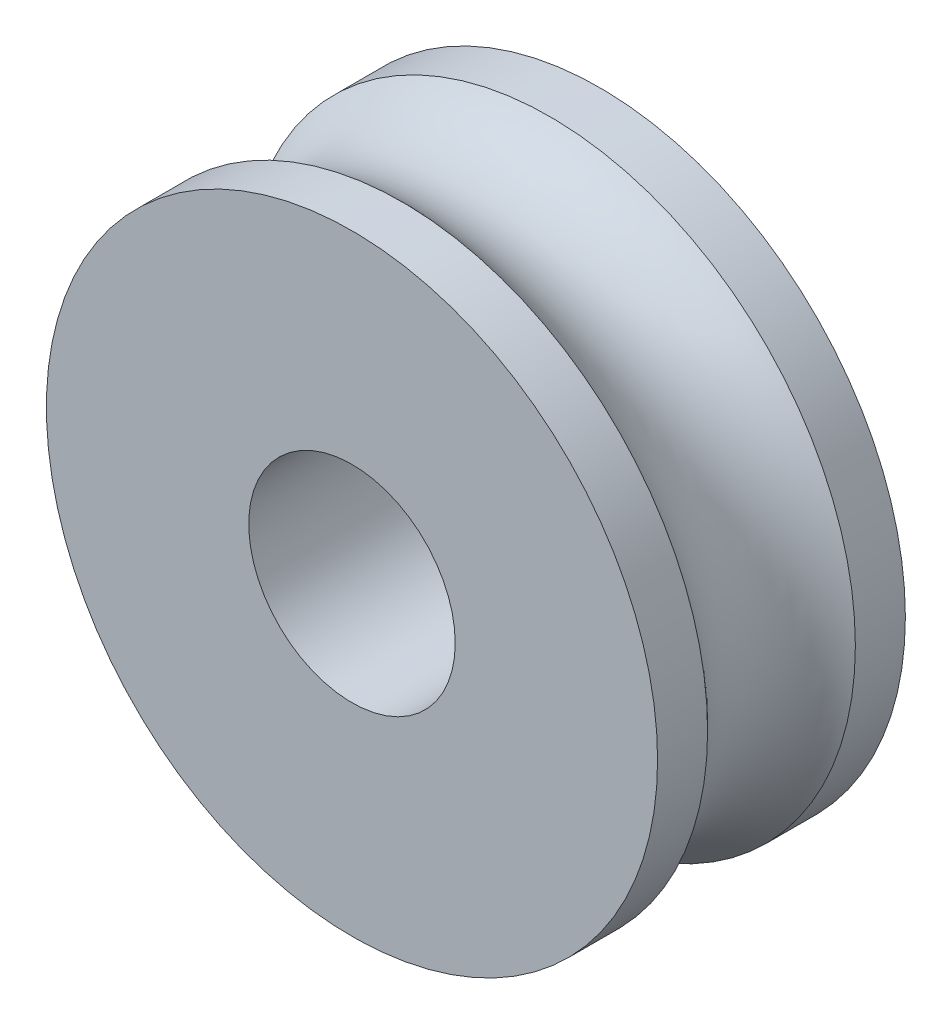
SolidWorks part; units mm, degrees
ref_plane "Front Plane" through (0, 0, 0) normal (0, 0, 1) x (1, 0, 0)
ref_plane "Top Plane" through (0, 0, 0) normal (0, 1, 0) x (1, 0, 0)
ref_plane "Right Plane" through (0, 0, 0) normal (1, 0, 0) x (0, 0, -1)
sketch "Sketch1" plane through (0, 0, 0) normal (1, 0, 0) x (0, 0, -1)
  line L0 (0, 0) -> (0, 24.75) construction
  line L1 (0, 0) -> (65.7769, 0) construction
  line L6 (15, 12.5) -> (-15, 12.5)
  line L7 (15, 12.5) -> (15, 37)
  line L9 (15, 37) -> (8.9443, 37)
  line L10 (-15, 12.5) -> (-15, 37)
  line L11 (15, 12.5) -> (-15, 37) construction
  line L12 (15, 37) -> (-15, 12.5) construction
  line L13 (-8.9443, 37) -> (-15, 37)
  arc A2 (8.9443, 37) -> (-8.9443, 37) centre (0, 45) cw
  dimension "D4" = 12
  dimension "D1" = 30
  dimension "D2" = 37
  dimension "D3" = 8
  dimension "D5" = 12.5
revolve "Revolve1" add sketch "Sketch1" angle 360 about L1
